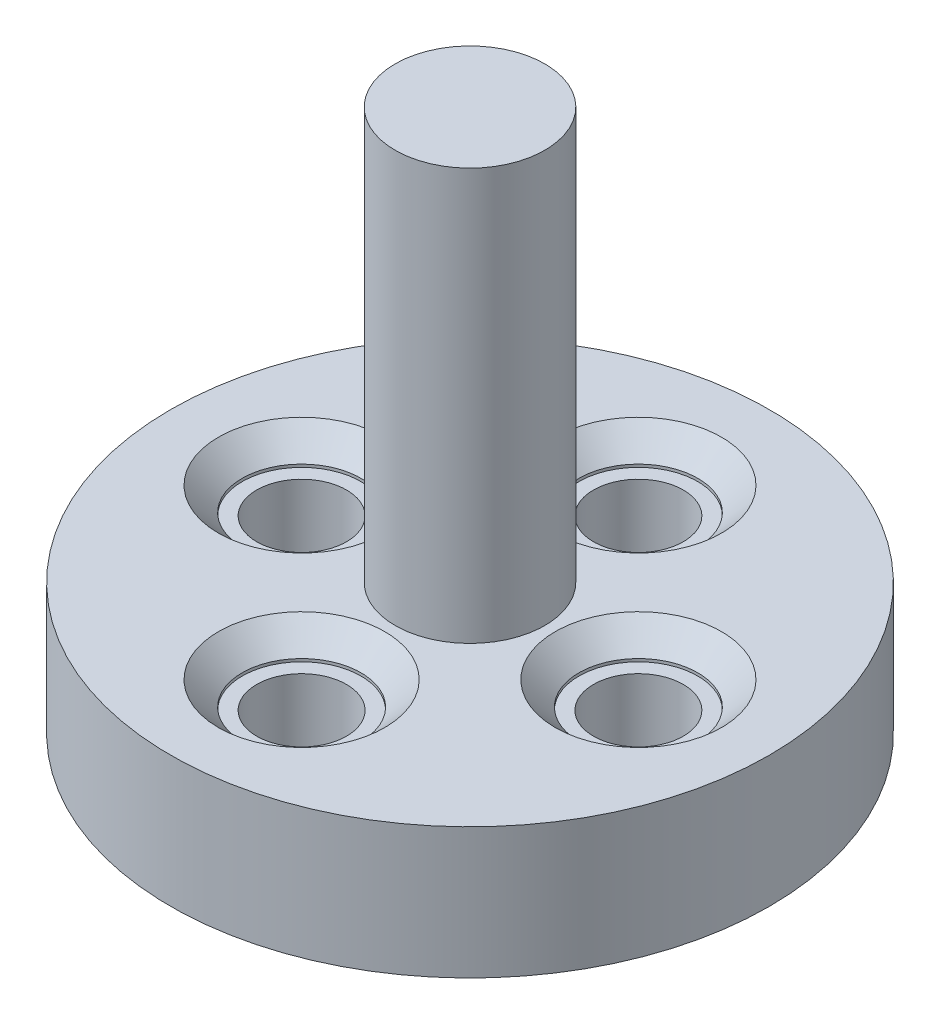
SolidWorks part; units mm, degrees
ref_plane "Front Plane" through (0, 0, 0) normal (0, 0, 1) x (1, 0, 0)
ref_plane "Top Plane" through (0, 0, 0) normal (0, 1, 0) x (1, 0, 0)
ref_plane "Right Plane" through (0, 0, 0) normal (1, 0, 0) x (0, 0, -1)
sketch "Sketch1" plane through (0, 0, 0) normal (0, 0, 1) x (1, 0, 0)
  line L0 (-5.8137, 6.85) -> (-5.8137, -7.65)
  line L1 (-5.8137, -7.65) -> (2.1863, -7.65)
  line L2 (2.1863, -7.65) -> (2.1863, -4.15)
  line L3 (2.1863, -4.15) -> (-3.8137, -4.15)
  line L4 (-3.8137, -4.15) -> (-3.8137, 6.85)
  line L5 (-3.8137, 6.85) -> (-5.8137, 6.85)
  dimension "D1" = 8
  dimension "D2" = 14.5
  dimension "D3" = 11
  dimension "D4" = 2
revolve "Revolve1" add sketch "Sketch1" angle 360 about L0
sketch "Sketch2" plane through (0, -4.15, 0) normal (0, 1, 0) x (1, 0, 0)
  circle A0 centre (-5.8137, 0) radius 4.5
  dimension "D1" = 9
hole_wizard "CBORE for #00 Binding Head Machine Screw1" positions "Sketch9" profile "Sketch7" counterbore size "#00" standard "ANSI Inch"
sketch "Sketch9" plane through (0, -4.15, 0) normal (0, 1, 0) x (1, 0, 0)
  circle A0 centre (-5.8137, 0) radius 4.5 construction
  point P0 (-10.3137, 0)
  point P4 (-5.8137, 4.5)
  point P6 (-1.3137, 0)
  point P8 (-5.8137, -4.5)
sketch "Sketch7" plane through (-10.3137, -4.15, 0) normal (1, 0, 0) x (0, 0, 1)
  line L0 (0, 0) -> (0, 0.4697)
  line L1 (0, 0.4697) -> (0.6985, 0.05)
  line L2 (0.6985, 0.05) -> (0.6985, 0.7112)
  line L3 (0.6985, 0.7112) -> (1.5875, 0.7112)
  line L5 (1.5875, 0.7112) -> (1.5875, 0.635)
  line L6 (1.5875, 0.635) -> (2.2225, 0)
  line L7 (2.2225, 0) -> (0, 0)
  line L8 (-1.5875, 0.635) -> (-2.2225, 0) construction
  line L10 (0, 0.4697) -> (-0.6985, 0.05) construction
  line L11 (0, -6.35) -> (0, 107.95) construction
  dimension "Hole Dia." = 1.397
  dimension "Hole Depth" = 0.05
  dimension "C'Bore Dia." = 3.175
  dimension "C'Bore Depth" = 0.7112
  dimension "Near C'Sink Dia." = 4.445
  dimension "Near C'Sink Angle" = 90
  dimension "Drill Angle" = 118
sketch "Sketch10" plane through (0, -4.15, 0) normal (0, 1, 0) x (1, 0, 0)
  circle A0 centre (-10.3137, 0) radius 1.2
  circle A1 centre (-5.8137, 4.5) radius 1.2
  circle A2 centre (-1.3137, 0) radius 1.2
  circle A4 centre (-5.8137, -4.5) radius 1.2
  dimension "D1" = 2.4
extrude "Cut-Extrude1" cut sketch "Sketch10" against normal through all
sketch "Sketch11" plane through (0, -7.65, 0) normal (0, -1, 0) x (1, 0, 0)
  circle A0 centre (-5.8137, 0) radius 1.2667
extrude "Cut-Extrude2" cut sketch "Sketch11" against normal blind 4
